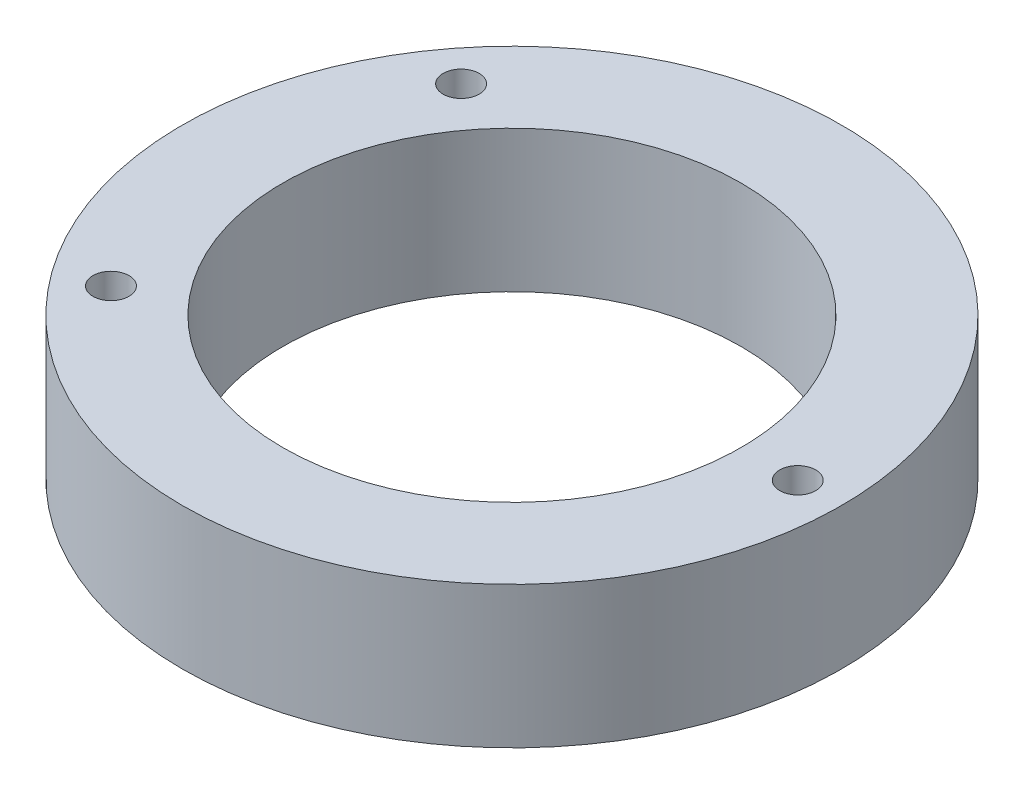
SolidWorks part; units mm, degrees
ref_plane "Front" through (0, 0, 0) normal (0, 0, 1) x (1, 0, 0)
ref_plane "Top" through (0, 0, 0) normal (0, 1, 0) x (1, 0, 0)
ref_plane "Right" through (0, 0, 0) normal (1, 0, 0) x (0, 0, -1)
sketch "Sketch2" plane through (0, 0, 0) normal (0, 1, 0) x (1, 0, 0)
  line L0 (0, 0) -> (-21.9327, -17.0005) construction
  line L1 (0, 0) -> (-21.9327, 17.0005) construction
  line L2 (0, 0) -> (27.75, 0) construction
  line L3 (-21.9327, 17.0005) -> (-21.9327, -17.0005) construction
  circle A0 centre (0, 0) radius 32
  circle A1 centre (0, 0) radius 22.25
  circle A2 centre (27.75, 0) radius 1.75
  circle A3 centre (-21.9327, -17.0005) radius 1.75
  circle A4 centre (-21.9327, 17.0005) radius 1.75
  dimension "D1" = 64
  dimension "D2" = 44.5
  dimension "D5" = 3.5
  dimension "D3" = 75.56
  dimension "D4" = 27.75
extrude "Boss-Extrude1" add sketch "Sketch2" along normal blind 13.75
